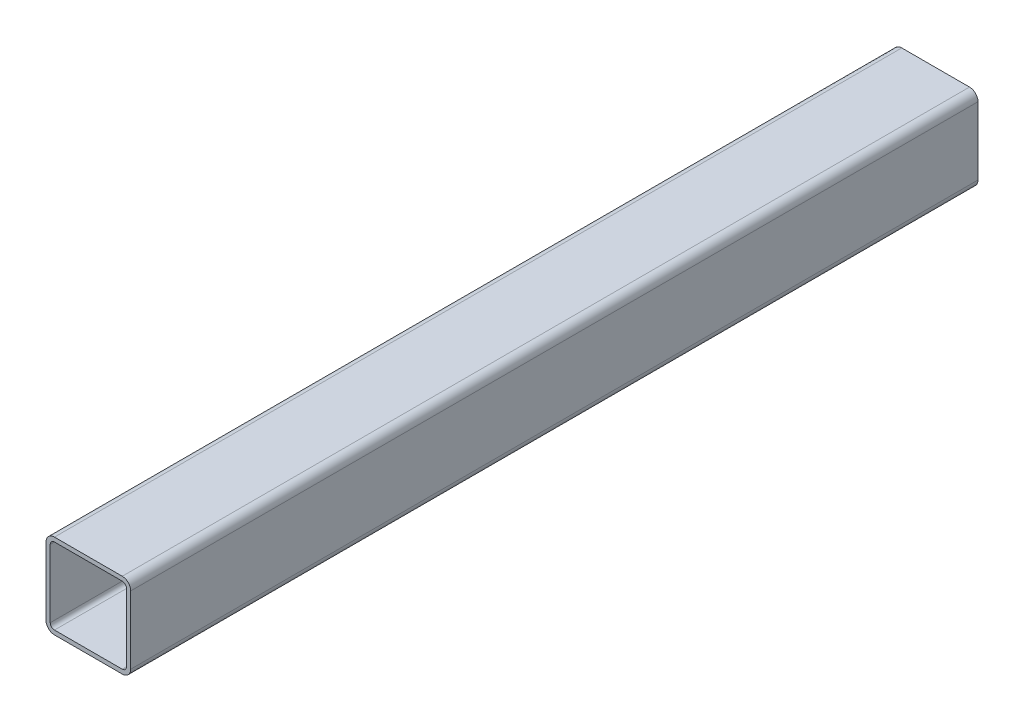
SolidWorks part; units mm, degrees
material "S355 verification"
ref_plane "Front Plane" through (0, 0, 0) normal (0, 0, 1) x (1, 0, 0)
ref_plane "Top Plane" through (0, 0, 0) normal (0, 1, 0) x (1, 0, 0)
ref_plane "Right Plane" through (0, 0, 0) normal (1, 0, 0) x (0, 0, -1)
sketch "Sketch1" plane through (0, 0, 0) normal (0, 1, 0) x (1, 0, 0)
  line L0 (0, 0) -> (0, -1000)
other "SHS100x100x5 (1)"
ref_plane "Plane1" through (0, 0, 0) normal (0, 0, 1) x (1, 0, 0)
sketch "Sketch11" plane through (0, 0, 0) normal (0, 0, 1) x (1, 0, 0)
  line L0 (-40, -50) -> (40, -50)
  line L1 (50, -40) -> (50, 40)
  line L2 (40, 50) -> (-40, 50)
  line L3 (-50, 40) -> (-50, -40)
  line L4 (-40, -45) -> (40, -45)
  line L5 (45, -40) -> (45, 40)
  line L6 (40, 45) -> (-40, 45)
  line L7 (-45, 40) -> (-45, -40)
  arc A0 (40, -50) -> (50, -40) centre (40, -40) ccw
  arc A1 (50, 40) -> (40, 50) centre (40, 40) ccw
  arc A2 (-40, 50) -> (-50, 40) centre (-40, 40) ccw
  arc A3 (-50, -40) -> (-40, -50) centre (-40, -40) ccw
  arc A4 (40, -45) -> (45, -40) centre (40, -40) ccw
  arc A5 (45, 40) -> (40, 45) centre (40, 40) ccw
  arc A6 (-40, 45) -> (-45, 40) centre (-40, 40) ccw
  arc A7 (-45, -40) -> (-40, -45) centre (-40, -40) ccw
  point P20 (0, 0)
